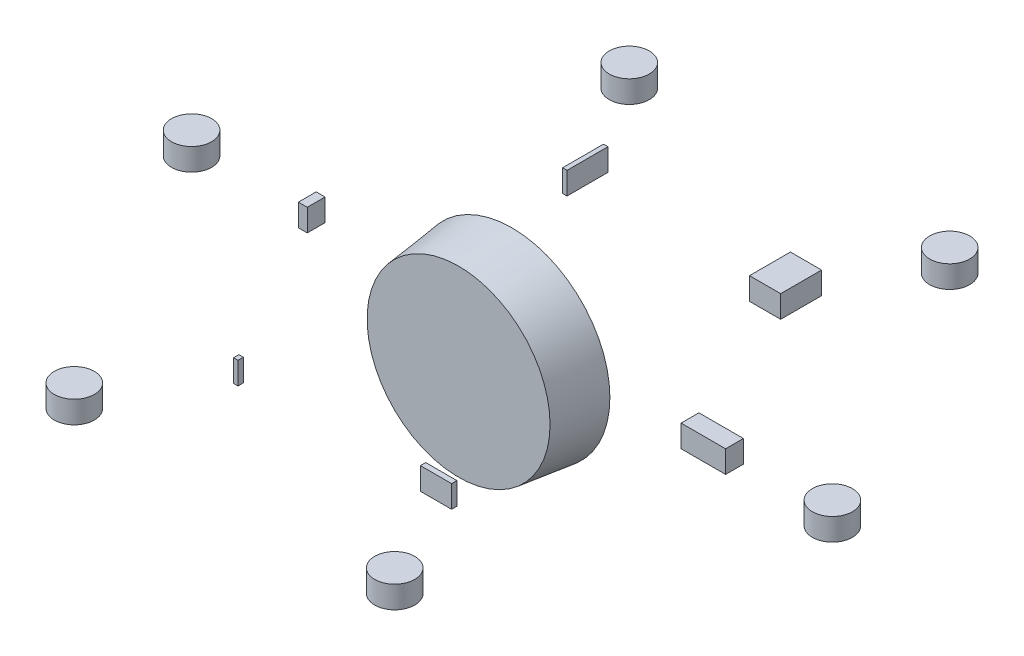
SolidWorks part; units mm, degrees
ref_plane "Front Plane" through (0, 0, 0) normal (0, 0, 1) x (1, 0, 0)
ref_plane "Top Plane" through (0, 0, 0) normal (0, 1, 0) x (1, 0, 0)
ref_plane "Right Plane" through (0, 0, 0) normal (1, 0, 0) x (0, 0, -1)
other "Graphic1"
other "Graphic (Closed) -1"
other "Graphic (Closed) -2"
other "Graphic (Closed) -3"
other "Graphic (Closed) -4"
other "Graphic (Closed) -5"
other "Graphic (Closed) -6"
other "Graphic (Closed) -7"
other "Graphic (Closed) -8"
other "Graphic (Closed) -9"
other "Graphic (Closed) -10"
other "Graphic (Closed) -11"
other "Graphic (Closed) -12"
other "Graphic (Open) -1"
other "Graphic (Open) -2"
other "Graphic (Open) -3"
other "Graphic (Open) -4"
other "Graphic (Open) -5"
other "Graphic (Open) -6"
other "Graphic (Open) -7"
other "Graphic (Open) -8"
other "Graphic (Open) -9"
other "Graphic (Open) -10"
other "Graphic (Open) -11"
other "Graphic (Open) -12"
other "Graphic (Open) -13"
other "Graphic (Open) -14"
other "Graphic (Open) -15"
other "Graphic (Open) -16"
other "Graphic (Open) -17"
other "Graphic (Open) -18"
sketch "Sketch1" plane through (0, 0, 0) normal (0, 0, 1) x (1, 0, 0)
  circle A0 centre (0, 0) radius 220
extrude "Boss-Extrude1" add sketch "Sketch1" along normal blind 120 draft 6.875
sketch "Sketch2" plane through (0, 0, 0) normal (0, 1, 0) x (1, 0, 0)
  line L1 (400, -20) -> (500, -20)
  line L2 (400, -20) -> (400, 20)
  line L3 (400, 20) -> (500, 20)
  line L4 (500, -20) -> (500, 20)
  line L5 (400, -20) -> (500, 20) construction
  line L6 (400, 20) -> (500, -20) construction
  line L7 (190, 343.7307) -> (260, 343.7307)
  line L8 (190, 343.7307) -> (190, 435.6922)
  line L9 (190, 435.6922) -> (260, 435.6922)
  line L10 (260, 343.7307) -> (260, 435.6922)
  line L11 (190, 343.7307) -> (260, 435.6922) construction
  line L12 (190, 435.6922) -> (260, 343.7307) construction
  line L13 (-230, 343.7307) -> (-220, 343.7307)
  line L14 (-230, 343.7307) -> (-230, 435.6922)
  line L15 (-230, 435.6922) -> (-220, 435.6922)
  line L16 (-220, 343.7307) -> (-220, 435.6922)
  line L17 (-230, 343.7307) -> (-220, 435.6922) construction
  line L18 (-230, 435.6922) -> (-220, 343.7307) construction
  line L19 (-440, -20) -> (-460, -20)
  line L20 (-440, -20) -> (-440, 20)
  line L21 (-440, 20) -> (-460, 20)
  line L22 (-460, -20) -> (-460, 20)
  line L23 (-440, -20) -> (-460, 20) construction
  line L24 (-440, 20) -> (-460, -20) construction
  line L25 (-230, -383.7307) -> (-220, -383.7307)
  line L26 (-230, -383.7307) -> (-230, -395.6922)
  line L27 (-230, -395.6922) -> (-220, -395.6922)
  line L28 (-220, -383.7307) -> (-220, -395.6922)
  line L29 (-230, -383.7307) -> (-220, -395.6922) construction
  line L30 (-230, -395.6922) -> (-220, -383.7307) construction
  line L31 (190, -383.7307) -> (260, -383.7307)
  line L32 (190, -383.7307) -> (190, -395.6922)
  line L33 (190, -395.6922) -> (260, -395.6922)
  line L34 (260, -383.7307) -> (260, -395.6922)
  line L35 (190, -383.7307) -> (260, -395.6922) construction
  line L36 (190, -395.6922) -> (260, -383.7307) construction
  circle A0 centre (720, 0) radius 45
  circle A1 centre (360, 623.5383) radius 45
  circle A2 centre (-360, 623.5383) radius 45
  circle A3 centre (-720, 0) radius 45
  circle A4 centre (-360, -623.5383) radius 45
  circle A5 centre (360, -623.5383) radius 45
  point P0 (450, 0)
  point P7 (225, 389.7114)
  point P14 (-225, 389.7114)
  point P21 (-450, 0)
  point P28 (-225, -389.7114)
  point P35 (225, -389.7114)
extrude "Boss-Extrude2" add sketch "Sketch2" along normal blind 50
